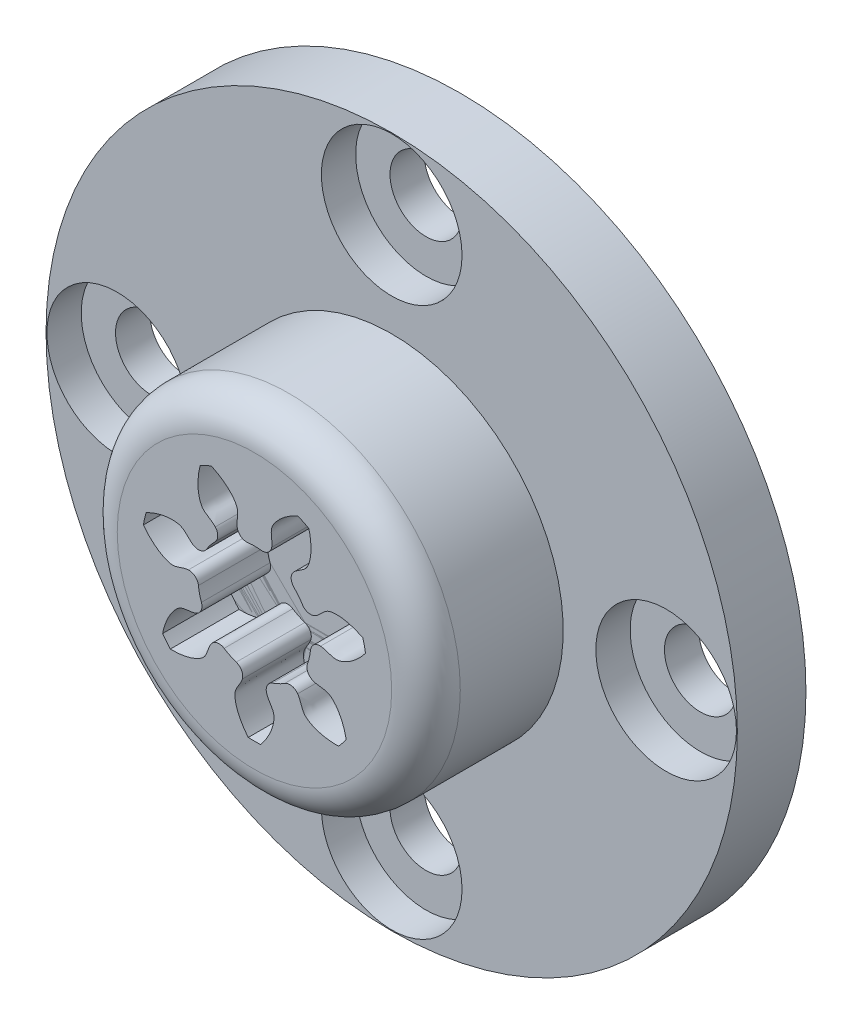
SolidWorks part; units mm, degrees
ref_plane "前视基准面" through (0, 0, 0) normal (0, 0, 1) x (1, 0, 0)
ref_plane "上视基准面" through (0, 0, 0) normal (0, 1, 0) x (1, 0, 0)
ref_plane "右视基准面" through (0, 0, 0) normal (1, 0, 0) x (0, 0, -1)
other "Configuration Table"
ref_axis "Axis1" through (0, 0, -88.99) along (0, 0, 1)
sketch "草图1" plane through (0, 0, 0) normal (0, 0, 1) x (1, 0, 0)
  circle A0 centre (0, 0) radius 3.285
extrude "LaShenA" add sketch "草图1" along normal blind 7
sketch "SketchA" plane through (0, 0, 7) normal (0, 0, 1) x (1, 0, 0)
  line L0 (0, 0) -> (0, 3.285) construction
  arc A0 (0.1963, 1.6307) -> (-0.1963, 1.6307) centre (0, 0) ccw
  arc A1 (1.8169, 3.2085) -> (-1.8169, 3.2085) centre (0, 0) ccw
  arc A2 (-0.1963, 1.6307) -> (-0.5032, 1.8609) centre (-0.2295, 1.9061) cw
  arc A3 (0.5032, 1.8609) -> (0.1963, 1.6307) centre (0.2295, 1.9061) cw
  circle A4 centre (0, 0) radius 2.4009 construction
  circle A5 centre (0, 0) radius 3.285 construction
  circle A6 centre (0, 0) radius 1.6425 construction
  circle A7 centre (0, 0) radius 2.555 construction
  spline S0 degree 3 poles (0.5032, 1.8609) (0.5297, 2.0212) (0.4568, 2.201) (0.5104, 2.3697) (0.5181, 2.3886) (0.5257, 2.4056) (0.5354, 2.4254) (0.5475, 2.4478) (0.5621, 2.4727) (0.5795, 2.4999) (0.5999, 2.5291) (0.6233, 2.5603) (0.6501, 2.5933) (0.6803, 2.6278) (0.7141, 2.6635) (0.7517, 2.7004) (0.7931, 2.7381) (0.8385, 2.7764) (0.888, 2.8151) (0.9416, 2.8538) (0.9995, 2.8925) (1.0617, 2.9307) (1.1283, 2.9681) (1.1992, 3.0047) (1.2746, 3.0399) (1.3543, 3.0737) (1.4384, 3.1056) (1.5269, 3.1354) (1.6528, 3.1726) (1.7503, 3.1955) (1.8169, 3.2085) knots 0.126986 0.126986 0.126986 0.126986 0.327614 0.338803 0.3451 0.352797 0.361892 0.372388 0.384282 0.397576 0.412269 0.428362 0.445854 0.464745 0.485036 0.506726 0.529815 0.554304 0.580192 0.60748 0.636167 0.666253 0.697738 0.730623 0.764908 0.800591 0.837674 0.876157 0.916038 1 1 1 1
  spline S1 degree 3 poles (-0.5032, 1.8609) (-0.5297, 2.0212) (-0.4568, 2.201) (-0.5104, 2.3697) (-0.5181, 2.3886) (-0.5257, 2.4056) (-0.5354, 2.4254) (-0.5475, 2.4478) (-0.5621, 2.4727) (-0.5795, 2.4999) (-0.5999, 2.5291) (-0.6233, 2.5603) (-0.6501, 2.5933) (-0.6803, 2.6278) (-0.7141, 2.6635) (-0.7517, 2.7004) (-0.7931, 2.7381) (-0.8385, 2.7764) (-0.888, 2.8151) (-0.9416, 2.8538) (-0.9995, 2.8925) (-1.0617, 2.9307) (-1.1283, 2.9681) (-1.1992, 3.0047) (-1.2746, 3.0399) (-1.3543, 3.0737) (-1.4384, 3.1056) (-1.5269, 3.1354) (-1.6528, 3.1726) (-1.7503, 3.1955) (-1.8169, 3.2085) knots 0.126986 0.126986 0.126986 0.126986 0.327614 0.338803 0.3451 0.352797 0.361892 0.372388 0.384282 0.397576 0.412269 0.428362 0.445854 0.464745 0.485036 0.506726 0.529815 0.554304 0.580192 0.60748 0.636167 0.666253 0.697738 0.730623 0.764908 0.800591 0.837674 0.876157 0.916038 1 1 1 1
  dimension "D1" = 0.2774
  dimension "Db" = 4.8018
  dimension "Da" = 6.57
  dimension "Df" = 3.285
  dimension "Dn" = 5.11
extrude "Cut-ExtrudeA" cut sketch "SketchA" against normal blind 7
pattern_circular "www.KYTool.cn" count 7 over 360 about axis through (0, 0, -88.99) along (0, 0, 1) of "Cut-ExtrudeA"
sketch "草图3" plane through (0, 0, 7) normal (0, 0, 1) x (1, 0, 0)
  circle A0 centre (0, 0) radius 5
  arc A29 (-1.1525, 1.1702) -> (-1.1412, 1.5536) centre (-1.3472, 1.3679) ccw
  arc A30 (-1.2611, 3.0333) -> (-1.5852, 2.8772) centre (0, 0) ccw
  arc A31 (-0.5032, 1.8609) -> (-0.1963, 1.6307) centre (-0.2295, 1.9061) ccw
  arc A32 (0.1963, 1.6307) -> (-0.1963, 1.6307) centre (0, 0) ccw
  arc A33 (0.1963, 1.6307) -> (0.5032, 1.8609) centre (0.2295, 1.9061) ccw
  arc A34 (1.5852, 2.8772) -> (1.2611, 3.0333) centre (0, 0) ccw
  arc A35 (1.1412, 1.5536) -> (1.1525, 1.1702) centre (1.3472, 1.3679) ccw
  arc A36 (1.3974, 0.8633) -> (1.1525, 1.1702) centre (0, 0) ccw
  arc A37 (1.3974, 0.8633) -> (1.7686, 0.7668) centre (1.6334, 1.009) ccw
  arc A38 (3.2379, 0.5545) -> (3.1578, 0.9053) centre (0, 0) ccw
  arc A39 (1.9262, 0.0765) -> (1.6335, -0.1715) centre (1.9094, -0.2004) ccw
  arc A40 (1.5462, -0.5543) -> (1.6335, -0.1715) centre (0, 0) ccw
  arc A41 (1.5462, -0.5543) -> (1.7022, -0.9046) centre (1.8073, -0.6479) ccw
  arc A42 (2.4523, -2.1857) -> (2.6766, -1.9045) centre (0, 0) ccw
  arc A43 (1.2607, -1.4583) -> (0.8844, -1.3841) centre (1.0338, -1.6178) ccw
  arc A44 (0.5307, -1.5544) -> (0.8844, -1.3841) centre (0, 0) ccw
  arc A45 (0.5307, -1.5544) -> (0.3541, -1.8949) centre (0.6203, -1.8169) ccw
  arc A46 (-0.1799, -3.2801) -> (0.1799, -3.2801) centre (0, 0) ccw
  arc A47 (-0.3541, -1.8949) -> (-0.5307, -1.5544) centre (-0.6203, -1.8169) ccw
  arc A48 (-0.8844, -1.3841) -> (-0.5307, -1.5544) centre (0, 0) ccw
  arc A49 (-0.8844, -1.3841) -> (-1.2607, -1.4583) centre (-1.0338, -1.6178) ccw
  arc A50 (-2.6766, -1.9045) -> (-2.4523, -2.1857) centre (0, 0) ccw
  arc A51 (-1.7022, -0.9046) -> (-1.5462, -0.5543) centre (-1.8073, -0.6479) ccw
  arc A52 (-1.6335, -0.1715) -> (-1.5462, -0.5543) centre (0, 0) ccw
  arc A53 (-1.6335, -0.1715) -> (-1.9262, 0.0765) centre (-1.9094, -0.2004) ccw
  arc A54 (-3.1578, 0.9053) -> (-3.2379, 0.5545) centre (0, 0) ccw
  arc A55 (-1.7686, 0.7668) -> (-1.3974, 0.8633) centre (-1.6334, 1.009) ccw
  arc A56 (-1.1525, 1.1702) -> (-1.3974, 0.8633) centre (0, 0) ccw
  arc A57 (-1.1525, 1.1702) -> (-1.1412, 1.5536) centre (-1.3472, 1.3679) ccw
  arc A58 (-1.2611, 3.0333) -> (-1.5852, 2.8772) centre (0, 0) ccw
  arc A59 (-0.5032, 1.8609) -> (-0.1963, 1.6307) centre (-0.2295, 1.9061) ccw
  arc A60 (0.1963, 1.6307) -> (-0.1963, 1.6307) centre (0, 0) ccw
  arc A61 (0.1963, 1.6307) -> (0.5032, 1.8609) centre (0.2295, 1.9061) ccw
  arc A62 (1.5852, 2.8772) -> (1.2611, 3.0333) centre (0, 0) ccw
  arc A63 (1.1412, 1.5536) -> (1.1525, 1.1702) centre (1.3472, 1.3679) ccw
  arc A64 (1.3974, 0.8633) -> (1.1525, 1.1702) centre (0, 0) ccw
  arc A65 (1.3974, 0.8633) -> (1.7686, 0.7668) centre (1.6334, 1.009) ccw
  arc A66 (3.2379, 0.5545) -> (3.1578, 0.9053) centre (0, 0) ccw
  arc A67 (1.9262, 0.0765) -> (1.6335, -0.1715) centre (1.9094, -0.2004) ccw
  arc A68 (1.5462, -0.5543) -> (1.6335, -0.1715) centre (0, 0) ccw
  arc A69 (1.5462, -0.5543) -> (1.7022, -0.9046) centre (1.8073, -0.6479) ccw
  arc A70 (2.4523, -2.1857) -> (2.6766, -1.9045) centre (0, 0) ccw
  arc A71 (1.2607, -1.4583) -> (0.8844, -1.3841) centre (1.0338, -1.6178) ccw
  arc A72 (0.5307, -1.5544) -> (0.8844, -1.3841) centre (0, 0) ccw
  arc A73 (0.5307, -1.5544) -> (0.3541, -1.8949) centre (0.6203, -1.8169) ccw
  arc A74 (-0.1799, -3.2801) -> (0.1799, -3.2801) centre (0, 0) ccw
  arc A75 (-0.3541, -1.8949) -> (-0.5307, -1.5544) centre (-0.6203, -1.8169) ccw
  arc A76 (-0.8844, -1.3841) -> (-0.5307, -1.5544) centre (0, 0) ccw
  arc A77 (-0.8844, -1.3841) -> (-1.2607, -1.4583) centre (-1.0338, -1.6178) ccw
  arc A78 (-2.6766, -1.9045) -> (-2.4523, -2.1857) centre (0, 0) ccw
  arc A79 (-1.7022, -0.9046) -> (-1.5462, -0.5543) centre (-1.8073, -0.6479) ccw
  arc A80 (-1.6335, -0.1715) -> (-1.5462, -0.5543) centre (0, 0) ccw
  arc A81 (-1.6335, -0.1715) -> (-1.9262, 0.0765) centre (-1.9094, -0.2004) ccw
  arc A82 (-3.1578, 0.9053) -> (-3.2379, 0.5545) centre (0, 0) ccw
  arc A83 (-1.7686, 0.7668) -> (-1.3974, 0.8633) centre (-1.6334, 1.009) ccw
  arc A84 (-1.1525, 1.1702) -> (-1.3974, 0.8633) centre (0, 0) ccw
  spline S14 degree 3 poles (-5924.0499, -3724.9174) (221.023, -9.8323) (1.5877, 20.3237) (-1.6302, 2.6609) (-1.6452, 2.519) (-1.6491, 2.39) (-1.6439, 2.2746) (-1.6334, 2.1875) (-1.6222, 2.1251) (-1.6131, 2.0837) (-1.6033, 2.0459) (-1.5931, 2.0117) (-1.5827, 1.9812) (-1.5724, 1.9543) (-1.5624, 1.9308) (-1.553, 1.9109) (-1.5444, 1.8943) (-1.5345, 1.8765) (1.4413, -2.5699) (91.8418, 77.8135) (-4958.5333, -4938.6848) knots -21.91052 -21.91052 -21.91052 -21.91052 0.155554 0.219924 0.278697 0.331873 0.379451 0.421432 0.440323 0.457815 0.473908 0.488601 0.501895 0.51379 0.524285 0.533381 0.541077 0.547374 0.558563 7.133739 7.133739 7.133739 7.133739 only from (-1.5852, 2.8772) to (-1.1412, 1.5536)
  spline S15 degree 3 poles (6953.3411, 797.579) (-118.1053, -23.2899) (1.1106, -2.7293) (-0.5104, 2.3697) (-0.5181, 2.3886) (-0.5257, 2.4056) (-0.5354, 2.4254) (-0.5475, 2.4478) (-0.5621, 2.4727) (-0.5795, 2.4999) (-0.5999, 2.5291) (-0.6233, 2.5603) (-0.6501, 2.5933) (-0.6803, 2.6278) (-0.7141, 2.6635) (-0.7658, 2.7143) (-0.8238, 2.7649) (-0.9063, 2.8294) (-1.0017, 2.8954) (-16.0325, 11.7128) (-134.1104, -171.2281) (6633.5165, 2229.3453) knots -6.006917 -6.006917 -6.006917 -6.006917 0.568423 0.579612 0.585909 0.593605 0.602701 0.613196 0.625091 0.638385 0.653078 0.669171 0.686663 0.705554 0.725845 0.747535 0.795113 0.821001 0.876975 0.938547 22.358511 22.358511 22.358511 22.358511 only from (-0.5032, 1.8609) to (-1.2611, 3.0333)
  spline S16 degree 3 poles (-6605.8423, 2309.1607) (130.1184, -178.9331) (16.8797, 11.4303) (1.064, 2.9336) (0.9437, 2.8568) (0.8404, 2.7794) (0.7534, 2.7035) (0.6919, 2.6409) (0.6501, 2.5933) (0.6233, 2.5603) (0.5999, 2.5291) (0.5795, 2.4999) (0.5621, 2.4727) (0.5475, 2.4478) (0.5354, 2.4254) (0.5257, 2.4056) (0.5181, 2.3886) (0.5104, 2.3697) (-1.1105, -2.7292) (118.0994, -23.2889) (-6952.8142, 797.5179) knots -21.91052 -21.91052 -21.91052 -21.91052 0.155554 0.219924 0.278697 0.331873 0.379451 0.421432 0.440323 0.457815 0.473908 0.488601 0.501895 0.51379 0.524285 0.533381 0.541077 0.547374 0.558563 7.133739 7.133739 7.133739 7.133739 only from (1.2611, 3.0333) to (0.5032, 1.8609)
  spline S17 degree 3 poles (4958.9097, -4939.0586) (-91.8462, 77.8174) (-1.4414, -2.57) (1.5345, 1.8765) (1.5444, 1.8943) (1.553, 1.9109) (1.5624, 1.9308) (1.5724, 1.9543) (1.5827, 1.9812) (1.5931, 2.0117) (1.6033, 2.0459) (1.6131, 2.0837) (1.6222, 2.1251) (1.6303, 2.1703) (1.6372, 2.219) (1.6446, 2.291) (1.6481, 2.368) (1.647, 2.4726) (1.6392, 2.5884) (-0.8387, 19.8375) (-217.488, -1.9073) (5878.9023, -3796.318) knots -6.006917 -6.006917 -6.006917 -6.006917 0.568423 0.579612 0.585909 0.593605 0.602701 0.613196 0.625091 0.638385 0.653078 0.669171 0.686663 0.705554 0.725845 0.747535 0.795113 0.821001 0.876975 0.938547 22.358511 22.358511 22.358511 22.358511 only from (1.1412, 1.5536) to (1.5852, 2.8772)
  spline S18 degree 3 poles (-2313.3008, 6604.3937) (-58.7681, -213.2936) (19.4609, -6.0704) (2.9569, 0.9972) (2.822, 1.0434) (2.697, 1.0759) (2.5834, 1.0965) (2.4961, 1.1057) (2.4328, 1.1086) (2.3904, 1.109) (2.3514, 1.1079) (2.3158, 1.1055) (2.2837, 1.1022) (2.2552, 1.0981) (2.2301, 1.0936) (2.2085, 1.0889) (2.1905, 1.0842) (2.1709, 1.0784) (-2.8262, -0.8333) (55.4258, -106.8542) (-3711.4842, 5933.1733) knots -21.91052 -21.91052 -21.91052 -21.91052 0.155554 0.219924 0.278697 0.331873 0.379451 0.421432 0.440323 0.457815 0.473908 0.488601 0.501895 0.51379 0.524285 0.533381 0.541077 0.547374 0.558563 7.133739 7.133739 7.133739 7.133739 only from (3.1578, 0.9053) to (1.7686, 0.7668)
  spline S19 degree 3 poles (-769.6819, -6956.4844) (3.5749, 120.3267) (-2.908, -0.4754) (2.4239, -0.0297) (2.444, -0.0264) (2.4623, -0.0228) (2.4838, -0.0177) (2.5083, -0.0109) (2.5358, -0.0022) (2.5661, 0.0087) (2.5992, 0.022) (2.6349, 0.038) (2.6729, 0.0567) (2.7132, 0.0785) (2.7556, 0.1035) (2.8166, 0.1426) (2.8789, 0.1879) (2.9601, 0.254) (3.0457, 0.3323) (14.9867, 13.0242) (-137.0927, 168.8498) (697.3547, -6963.2764) knots -6.006917 -6.006917 -6.006917 -6.006917 0.568423 0.579612 0.585909 0.593605 0.602701 0.613196 0.625091 0.638385 0.653078 0.669171 0.686663 0.705554 0.725845 0.747535 0.795113 0.821001 0.876975 0.938547 22.358511 22.358511 22.358511 22.358511 only from (1.9262, 0.0765) to (3.2379, 0.5545)
  spline S20 degree 3 poles (3721.2034, 5926.3835) (-203.401, -87.0397) (7.3877, -18.9999) (2.6233, -1.6901) (2.5752, -1.5557) (2.5227, -1.4378) (2.468, -1.3361) (2.4208, -1.2622) (2.3836, -1.2108) (2.3574, -1.1774) (2.3322, -1.1476) (2.3082, -1.1213) (2.2856, -1.0983) (2.2646, -1.0785) (2.2455, -1.0617) (2.2283, -1.0478) (2.2134, -1.0366) (2.1967, -1.0249) (-2.4136, 1.69) (-48.9846, -109.9561) (2324.6691, 6601.0282) knots -21.91052 -21.91052 -21.91052 -21.91052 0.155554 0.219924 0.278697 0.331873 0.379451 0.421432 0.440323 0.457815 0.473908 0.488601 0.501895 0.51379 0.524285 0.533381 0.541077 0.547374 0.558563 7.133739 7.133739 7.133739 7.133739 only from (2.6766, -1.9045) to (1.7022, -0.9046)
  spline S21 degree 3 poles (-5918.6873, -3735.5355) (96.3041, 72.2275) (-2.1848, 1.9771) (1.488, -1.9136) (1.5031, -1.9272) (1.5174, -1.9393) (1.5347, -1.9529) (1.5554, -1.9679) (1.5793, -1.9839) (1.6068, -2.0008) (1.6378, -2.0184) (1.6725, -2.0363) (1.7109, -2.0544) (1.7531, -2.0724) (1.7991, -2.0899) (1.8676, -2.1132) (1.9419, -2.1337) (2.0441, -2.156) (2.1588, -2.1741) (19.5268, -3.5966) (46.5362, 212.4596) (-5009.3152, -4886.7457) knots -6.006917 -6.006917 -6.006917 -6.006917 0.568423 0.579612 0.585909 0.593605 0.602701 0.613196 0.625091 0.638385 0.653078 0.669171 0.686663 0.705554 0.725845 0.747535 0.795113 0.821001 0.876975 0.938547 22.358511 22.358511 22.358511 22.358511 only from (1.2607, -1.4583) to (2.4523, -2.1857)
  spline S22 degree 3 poles (6953.5656, 785.6857) (-194.8688, 104.7569) (-10.2486, -17.6222) (0.3142, -3.1047) (0.3893, -2.9834) (0.4488, -2.8688) (0.4942, -2.7626) (0.5225, -2.6796) (0.5395, -2.6185) (0.5493, -2.5772) (0.5569, -2.5389) (0.5625, -2.5037) (0.5664, -2.4717) (0.5688, -2.443) (0.57, -2.4175) (0.5701, -2.3955) (0.5696, -2.3768) (0.5683, -2.3565) (-0.1836, 2.9407) (-116.5086, -30.2589) (6610.2992, 2298.1743) knots -21.91052 -21.91052 -21.91052 -21.91052 0.155554 0.219924 0.278697 0.331873 0.379451 0.421432 0.440323 0.457815 0.473908 0.488601 0.501895 0.51379 0.524285 0.533381 0.541077 0.547374 0.558563 7.133739 7.133739 7.133739 7.133739 only from (0.1799, -3.2801) to (0.3541, -1.8949)
  spline S23 degree 3 poles (-6610.8004, 2298.3478) (116.5143, -30.2605) (0.1836, 2.9409) (-0.5683, -2.3565) (-0.5696, -2.3768) (-0.5701, -2.3955) (-0.57, -2.4175) (-0.5688, -2.443) (-0.5664, -2.4717) (-0.5625, -2.5037) (-0.5569, -2.5389) (-0.5493, -2.5772) (-0.5395, -2.6185) (-0.5272, -2.6627) (-0.5123, -2.7096) (-0.4877, -2.7777) (-0.4574, -2.8485) (-0.4111, -2.9424) (-0.3538, -3.0433) (9.3628, -17.5091) (195.1224, 96.0829) (-6943.8685, 869.6042) knots -6.006917 -6.006917 -6.006917 -6.006917 0.568423 0.579612 0.585909 0.593605 0.602701 0.613196 0.625091 0.638385 0.653078 0.669171 0.686663 0.705554 0.725845 0.747535 0.795113 0.821001 0.876975 0.938547 22.358511 22.358511 22.358511 22.358511 only from (-0.3541, -1.8949) to (-0.1799, -3.2801)
  spline S24 degree 3 poles (4949.751, -4946.6495) (-39.5964, 217.6694) (-20.1675, -2.9746) (-2.2314, -2.1814) (-2.0898, -2.1645) (-1.9631, -2.1395) (-1.8518, -2.1088) (-1.7692, -2.0792) (-1.7109, -2.0544) (-1.6725, -2.0363) (-1.6378, -2.0184) (-1.6068, -2.0008) (-1.5793, -1.9839) (-1.5554, -1.9679) (-1.5347, -1.9529) (-1.5174, -1.9393) (-1.5031, -1.9272) (-1.488, -1.9136) (2.1847, 1.977) (-96.2992, 72.224) (5918.2391, -3735.2518) knots -21.91052 -21.91052 -21.91052 -21.91052 0.155554 0.219924 0.278697 0.331873 0.379451 0.421432 0.440323 0.457815 0.473908 0.488601 0.501895 0.51379 0.524285 0.533381 0.541077 0.547374 0.558563 7.133739 7.133739 7.133739 7.133739 only from (-2.4523, -2.1857) to (-1.2607, -1.4583)
  spline S25 degree 3 poles (-2324.846, 6601.5283) (48.9869, -109.9617) (2.4137, 1.6901) (-2.1967, -1.0249) (-2.2134, -1.0366) (-2.2283, -1.0478) (-2.2455, -1.0617) (-2.2646, -1.0785) (-2.2856, -1.0983) (-2.3082, -1.1213) (-2.3322, -1.1476) (-2.3574, -1.1774) (-2.3836, -1.2108) (-2.4105, -1.248) (-2.4378, -1.2889) (-2.4758, -1.3506) (-2.5123, -1.4184) (-2.5568, -1.5131) (-2.5999, -1.6209) (-7.8515, -18.2369) (196.7775, -92.6461) (-3649.5473, 5971.1244) knots -6.006917 -6.006917 -6.006917 -6.006917 0.568423 0.579612 0.585909 0.593605 0.602701 0.613196 0.625091 0.638385 0.653078 0.669171 0.686663 0.705554 0.725845 0.747535 0.795113 0.821001 0.876975 0.938547 22.358511 22.358511 22.358511 22.358511 only from (-1.7022, -0.9046) to (-2.6766, -1.9045)
  spline S26 degree 3 poles (-781.327, -6954.0567) (145.4928, 166.6724) (-14.8998, 13.913) (-3.0968, 0.3845) (-2.9952, 0.2843) (-2.8968, 0.2009) (-2.8033, 0.133) (-2.7287, 0.0868) (-2.6729, 0.0567) (-2.6349, 0.038) (-2.5992, 0.022) (-2.5661, 0.0087) (-2.5358, -0.0022) (-2.5083, -0.0109) (-2.4838, -0.0177) (-2.4623, -0.0228) (-2.444, -0.0264) (-2.4239, -0.0297) (2.9079, -0.4754) (-3.5746, 120.3207) (769.6243, -6955.9571) knots -21.91052 -21.91052 -21.91052 -21.91052 0.155554 0.219924 0.278697 0.331873 0.379451 0.421432 0.440323 0.457815 0.473908 0.488601 0.501895 0.51379 0.524285 0.533381 0.541077 0.547374 0.558563 7.133739 7.133739 7.133739 7.133739 only from (-3.2379, 0.5545) to (-1.9262, 0.0765)
  spline S27 degree 3 poles (3711.7649, 5933.6234) (-55.4287, -106.8595) (2.8263, -0.8334) (-2.1709, 1.0784) (-2.1905, 1.0842) (-2.2085, 1.0889) (-2.2301, 1.0936) (-2.2552, 1.0981) (-2.2837, 1.1022) (-2.3158, 1.1055) (-2.3514, 1.1079) (-2.3904, 1.109) (-2.4328, 1.1086) (-2.4786, 1.1065) (-2.5277, 1.1024) (-2.5996, 1.0936) (-2.6753, 1.0798) (-2.7771, 1.0555) (-2.8883, 1.0221) (-19.1535, -5.232) (50.2551, -211.6108) (2392.9575, 6576.2661) knots -6.006917 -6.006917 -6.006917 -6.006917 0.568423 0.579612 0.585909 0.593605 0.602701 0.613196 0.625091 0.638385 0.653078 0.669171 0.686663 0.705554 0.725845 0.747535 0.795113 0.821001 0.876975 0.938547 22.358511 22.358511 22.358511 22.358511 only from (-1.7686, 0.7668) to (-3.1578, 0.9053)
  spline S28 degree 3 poles (-1.5852, 2.8772) (-1.5909, 2.8548) (-1.6082, 2.7817) (-1.6302, 2.6609) (-1.6452, 2.519) (-1.6491, 2.39) (-1.6439, 2.2746) (-1.6334, 2.1875) (-1.6222, 2.1251) (-1.6131, 2.0837) (-1.6033, 2.0459) (-1.5931, 2.0117) (-1.5827, 1.9812) (-1.5724, 1.9543) (-1.5624, 1.9308) (-1.553, 1.9109) (-1.5444, 1.8943) (-1.5345, 1.8765) (-1.436, 1.7294) (-1.25, 1.6743) (-1.1412, 1.5536) knots 0.126986 0.126986 0.126986 0.126986 0.155554 0.219924 0.278697 0.331873 0.379451 0.421432 0.440323 0.457815 0.473908 0.488601 0.501895 0.51379 0.524285 0.533381 0.541077 0.547374 0.558563 0.759191 0.759191 0.759191 0.759191
  spline S29 degree 3 poles (-0.5032, 1.8609) (-0.5297, 2.0212) (-0.4568, 2.201) (-0.5104, 2.3697) (-0.5181, 2.3886) (-0.5257, 2.4056) (-0.5354, 2.4254) (-0.5475, 2.4478) (-0.5621, 2.4727) (-0.5795, 2.4999) (-0.5999, 2.5291) (-0.6233, 2.5603) (-0.6501, 2.5933) (-0.6803, 2.6278) (-0.7141, 2.6635) (-0.7658, 2.7143) (-0.8238, 2.7649) (-0.9063, 2.8294) (-1.0017, 2.8954) (-1.1266, 2.9687) (-1.2158, 3.0128) (-1.2611, 3.0333) knots 0.367795 0.367795 0.367795 0.367795 0.568423 0.579612 0.585909 0.593605 0.602701 0.613196 0.625091 0.638385 0.653078 0.669171 0.686663 0.705554 0.725845 0.747535 0.795113 0.821001 0.876975 0.938547 1 1 1 1
  spline S30 degree 3 poles (1.2611, 3.0333) (1.2401, 3.0238) (1.1721, 2.9917) (1.064, 2.9336) (0.9437, 2.8568) (0.8404, 2.7794) (0.7534, 2.7035) (0.6919, 2.6409) (0.6501, 2.5933) (0.6233, 2.5603) (0.5999, 2.5291) (0.5795, 2.4999) (0.5621, 2.4727) (0.5475, 2.4478) (0.5354, 2.4254) (0.5257, 2.4056) (0.5181, 2.3886) (0.5104, 2.3697) (0.4568, 2.201) (0.5297, 2.0212) (0.5032, 1.8609) knots 0.126986 0.126986 0.126986 0.126986 0.155554 0.219924 0.278697 0.331873 0.379451 0.421432 0.440323 0.457815 0.473908 0.488601 0.501895 0.51379 0.524285 0.533381 0.541077 0.547374 0.558563 0.759191 0.759191 0.759191 0.759191
  spline S31 degree 3 poles (1.1412, 1.5536) (1.25, 1.6743) (1.436, 1.7294) (1.5345, 1.8765) (1.5444, 1.8943) (1.553, 1.9109) (1.5624, 1.9308) (1.5724, 1.9543) (1.5827, 1.9812) (1.5931, 2.0117) (1.6033, 2.0459) (1.6131, 2.0837) (1.6222, 2.1251) (1.6303, 2.1703) (1.6372, 2.219) (1.6446, 2.291) (1.6481, 2.368) (1.647, 2.4726) (1.6392, 2.5884) (1.6186, 2.7318) (1.5974, 2.829) (1.5852, 2.8772) knots 0.367795 0.367795 0.367795 0.367795 0.568423 0.579612 0.585909 0.593605 0.602701 0.613196 0.625091 0.638385 0.653078 0.669171 0.686663 0.705554 0.725845 0.747535 0.795113 0.821001 0.876975 0.938547 1 1 1 1
  spline S32 degree 3 poles (3.1578, 0.9053) (3.1372, 0.9158) (3.0698, 0.9489) (2.9569, 0.9972) (2.822, 1.0434) (2.697, 1.0759) (2.5834, 1.0965) (2.4961, 1.1057) (2.4328, 1.1086) (2.3904, 1.109) (2.3514, 1.1079) (2.3158, 1.1055) (2.2837, 1.1022) (2.2552, 1.0981) (2.2301, 1.0936) (2.2085, 1.0889) (2.1905, 1.0842) (2.1709, 1.0784) (2.0056, 1.0152) (1.9105, 0.8461) (1.7686, 0.7668) knots 0.126986 0.126986 0.126986 0.126986 0.155554 0.219924 0.278697 0.331873 0.379451 0.421432 0.440323 0.457815 0.473908 0.488601 0.501895 0.51379 0.524285 0.533381 0.541077 0.547374 0.558563 0.759191 0.759191 0.759191 0.759191
  spline S33 degree 3 poles (1.9262, 0.0765) (2.0884, 0.0666) (2.2475, -0.0444) (2.4239, -0.0297) (2.444, -0.0264) (2.4623, -0.0228) (2.4838, -0.0177) (2.5083, -0.0109) (2.5358, -0.0022) (2.5661, 0.0087) (2.5992, 0.022) (2.6349, 0.038) (2.6729, 0.0567) (2.7132, 0.0785) (2.7556, 0.1035) (2.8166, 0.1426) (2.8789, 0.1879) (2.9601, 0.254) (3.0457, 0.3323) (3.145, 0.4378) (3.2078, 0.515) (3.2379, 0.5545) knots 0.367795 0.367795 0.367795 0.367795 0.568423 0.579612 0.585909 0.593605 0.602701 0.613196 0.625091 0.638385 0.653078 0.669171 0.686663 0.705554 0.725845 0.747535 0.795113 0.821001 0.876975 0.938547 1 1 1 1
  spline S34 degree 3 poles (2.6766, -1.9045) (2.672, -1.8818) (2.6558, -1.8084) (2.6233, -1.6901) (2.5752, -1.5557) (2.5227, -1.4378) (2.468, -1.3361) (2.4208, -1.2622) (2.3836, -1.2108) (2.3574, -1.1774) (2.3322, -1.1476) (2.3082, -1.1213) (2.2856, -1.0983) (2.2646, -1.0785) (2.2455, -1.0617) (2.2283, -1.0478) (2.2134, -1.0366) (2.1967, -1.0249) (2.0442, -0.9351) (1.8526, -0.9662) (1.7022, -0.9046) knots 0.126986 0.126986 0.126986 0.126986 0.155554 0.219924 0.278697 0.331873 0.379451 0.421432 0.440323 0.457815 0.473908 0.488601 0.501895 0.51379 0.524285 0.533381 0.541077 0.547374 0.558563 0.759191 0.759191 0.759191 0.759191
  spline S35 degree 3 poles (1.2607, -1.4583) (1.3542, -1.5912) (1.3665, -1.7848) (1.488, -1.9136) (1.5031, -1.9272) (1.5174, -1.9393) (1.5347, -1.9529) (1.5554, -1.9679) (1.5793, -1.9839) (1.6068, -2.0008) (1.6378, -2.0184) (1.6725, -2.0363) (1.7109, -2.0544) (1.7531, -2.0724) (1.7991, -2.0899) (1.8676, -2.1132) (1.9419, -2.1337) (2.0441, -2.156) (2.1588, -2.1741) (2.3031, -2.1859) (2.4026, -2.1869) (2.4523, -2.1857) knots 0.367795 0.367795 0.367795 0.367795 0.568423 0.579612 0.585909 0.593605 0.602701 0.613196 0.625091 0.638385 0.653078 0.669171 0.686663 0.705554 0.725845 0.747535 0.795113 0.821001 0.876975 0.938547 1 1 1 1
  spline S36 degree 3 poles (0.1799, -3.2801) (0.1947, -3.2624) (0.242, -3.204) (0.3142, -3.1047) (0.3893, -2.9834) (0.4488, -2.8688) (0.4942, -2.7626) (0.5225, -2.6796) (0.5395, -2.6185) (0.5493, -2.5772) (0.5569, -2.5389) (0.5625, -2.5037) (0.5664, -2.4717) (0.5688, -2.443) (0.57, -2.4175) (0.5701, -2.3955) (0.5696, -2.3768) (0.5683, -2.3565) (0.5434, -2.1812) (0.3997, -2.0508) (0.3541, -1.8949) knots 0.126986 0.126986 0.126986 0.126986 0.155554 0.219924 0.278697 0.331873 0.379451 0.421432 0.440323 0.457815 0.473908 0.488601 0.501895 0.51379 0.524285 0.533381 0.541077 0.547374 0.558563 0.759191 0.759191 0.759191 0.759191
  spline S37 degree 3 poles (-0.3541, -1.8949) (-0.3997, -2.0508) (-0.5434, -2.1812) (-0.5683, -2.3565) (-0.5696, -2.3768) (-0.5701, -2.3955) (-0.57, -2.4175) (-0.5688, -2.443) (-0.5664, -2.4717) (-0.5625, -2.5037) (-0.5569, -2.5389) (-0.5493, -2.5772) (-0.5395, -2.6185) (-0.5272, -2.6627) (-0.5123, -2.7096) (-0.4877, -2.7777) (-0.4574, -2.8485) (-0.4111, -2.9424) (-0.3538, -3.0433) (-0.273, -3.1635) (-0.2118, -3.242) (-0.1799, -3.2801) knots 0.367795 0.367795 0.367795 0.367795 0.568423 0.579612 0.585909 0.593605 0.602701 0.613196 0.625091 0.638385 0.653078 0.669171 0.686663 0.705554 0.725845 0.747535 0.795113 0.821001 0.876975 0.938547 1 1 1 1
  spline S38 degree 3 poles (-2.4523, -2.1857) (-2.4292, -2.1863) (-2.3541, -2.1869) (-2.2314, -2.1814) (-2.0898, -2.1645) (-1.9631, -2.1395) (-1.8518, -2.1088) (-1.7692, -2.0792) (-1.7109, -2.0544) (-1.6725, -2.0363) (-1.6378, -2.0184) (-1.6068, -2.0008) (-1.5793, -1.9839) (-1.5554, -1.9679) (-1.5347, -1.9529) (-1.5174, -1.9393) (-1.5031, -1.9272) (-1.488, -1.9136) (-1.3665, -1.7848) (-1.3542, -1.5912) (-1.2607, -1.4583) knots 0.126986 0.126986 0.126986 0.126986 0.155554 0.219924 0.278697 0.331873 0.379451 0.421432 0.440323 0.457815 0.473908 0.488601 0.501895 0.51379 0.524285 0.533381 0.541077 0.547374 0.558563 0.759191 0.759191 0.759191 0.759191
  spline S39 degree 3 poles (-1.7022, -0.9046) (-1.8526, -0.9662) (-2.0442, -0.9351) (-2.1967, -1.0249) (-2.2134, -1.0366) (-2.2283, -1.0478) (-2.2455, -1.0617) (-2.2646, -1.0785) (-2.2856, -1.0983) (-2.3082, -1.1213) (-2.3322, -1.1476) (-2.3574, -1.1774) (-2.3836, -1.2108) (-2.4105, -1.248) (-2.4378, -1.2889) (-2.4758, -1.3506) (-2.5123, -1.4184) (-2.5568, -1.5131) (-2.5999, -1.6209) (-2.6436, -1.759) (-2.6667, -1.8558) (-2.6766, -1.9045) knots 0.367795 0.367795 0.367795 0.367795 0.568423 0.579612 0.585909 0.593605 0.602701 0.613196 0.625091 0.638385 0.653078 0.669171 0.686663 0.705554 0.725845 0.747535 0.795113 0.821001 0.876975 0.938547 1 1 1 1
  spline S40 degree 3 poles (-3.2379, 0.5545) (-3.2239, 0.5361) (-3.1775, 0.477) (-3.0968, 0.3845) (-2.9952, 0.2843) (-2.8968, 0.2009) (-2.8033, 0.133) (-2.7287, 0.0868) (-2.6729, 0.0567) (-2.6349, 0.038) (-2.5992, 0.022) (-2.5661, 0.0087) (-2.5358, -0.0022) (-2.5083, -0.0109) (-2.4838, -0.0177) (-2.4623, -0.0228) (-2.444, -0.0264) (-2.4239, -0.0297) (-2.2475, -0.0444) (-2.0884, 0.0666) (-1.9262, 0.0765) knots 0.126986 0.126986 0.126986 0.126986 0.155554 0.219924 0.278697 0.331873 0.379451 0.421432 0.440323 0.457815 0.473908 0.488601 0.501895 0.51379 0.524285 0.533381 0.541077 0.547374 0.558563 0.759191 0.759191 0.759191 0.759191
  spline S41 degree 3 poles (-1.7686, 0.7668) (-1.9105, 0.8461) (-2.0056, 1.0152) (-2.1709, 1.0784) (-2.1905, 1.0842) (-2.2085, 1.0889) (-2.2301, 1.0936) (-2.2552, 1.0981) (-2.2837, 1.1022) (-2.3158, 1.1055) (-2.3514, 1.1079) (-2.3904, 1.109) (-2.4328, 1.1086) (-2.4786, 1.1065) (-2.5277, 1.1024) (-2.5996, 1.0936) (-2.6753, 1.0798) (-2.7771, 1.0555) (-2.8883, 1.0221) (-3.0235, 0.9701) (-3.1136, 0.9279) (-3.1578, 0.9053) knots 0.367795 0.367795 0.367795 0.367795 0.568423 0.579612 0.585909 0.593605 0.602701 0.613196 0.625091 0.638385 0.653078 0.669171 0.686663 0.705554 0.725845 0.747535 0.795113 0.821001 0.876975 0.938547 1 1 1 1
  dimension "D1" = 0
  dimension "D2" = 10
extrude "凸台-拉伸2" add sketch "草图3" along normal blind 2 separate body
fillet "圆角1" radius 1 1 edges at (5, 0, 9)
sketch "草图5" plane through (0, 0, 7) normal (0, 0, -1) x (-1, 0, 0)
  circle A0 centre (0, 0) radius 5
extrude "凸台-拉伸3" add sketch "草图5" along normal blind 2
sketch "草图7" plane through (0, 0, 5) normal (0, 0, -1) x (-1, 0, 0)
  circle A0 centre (0, 0) radius 10.075
  dimension "D1" = 20.15
extrude "凸台-拉伸4" add sketch "草图7" along normal blind 2
sketch "草图8" plane through (0, 0, 5) normal (0, 0, 1) x (1, 0, 0)
  line L0 (0, 0) -> (8, 0) construction
  circle A0 centre (8, 0) radius 1.05
  circle A1 centre (0, -8) radius 1.05
  circle A2 centre (-8, 0) radius 1.05
  circle A3 centre (0, 8) radius 1.05
  point P13 (0, 0)
  dimension "D1" = 2.1
  dimension "D2" = 4
extrude "切除-拉伸1" cut sketch "草图8" against normal through all
sketch "草图9" plane through (0, 0, 5) normal (0, 0, 1) x (1, 0, 0)
  line L0 (0, 0) -> (0, 8)
  circle A0 centre (0, 8) radius 2.05
  circle A1 centre (8, 0) radius 2.05
  circle A2 centre (0, -8) radius 2.05
  circle A3 centre (-8, 0) radius 2.05
  point P14 (0, 0)
  dimension "D1" = 4
extrude "切除-拉伸2" cut sketch "草图9" against normal blind 1
sketch "草图10" plane through (0, 0, 7) normal (0, 0, 1) x (1, 0, 0)
  circle A0 centre (0, 0) radius 1.05
extrude "切除-拉伸3" cut sketch "草图10" against normal through all
